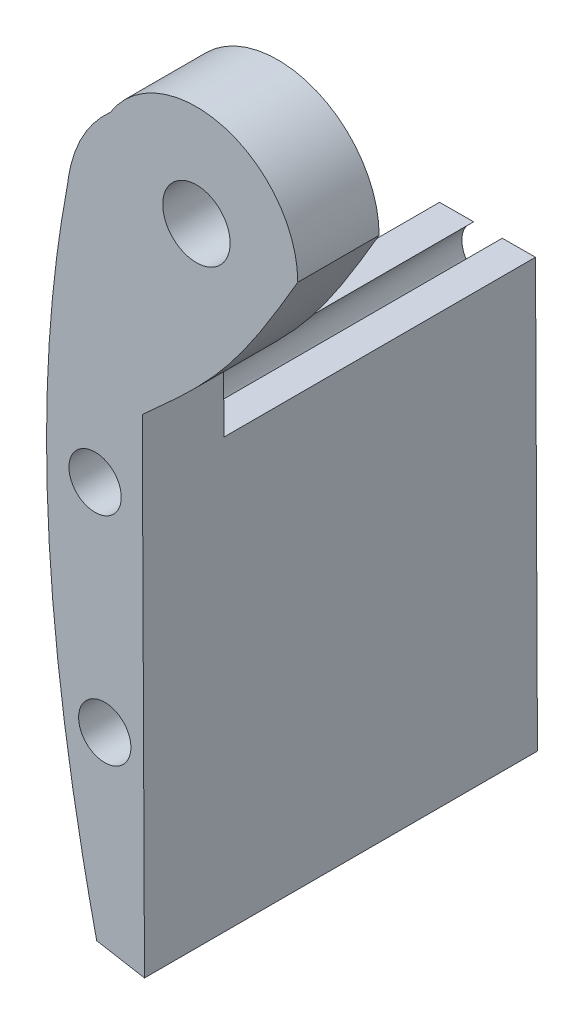
SolidWorks part; units mm, degrees
ref_plane "Front Plane" through (0, 0, 0) normal (0, 0, 1) x (1, 0, 0)
ref_plane "Top Plane" through (0, 0, 0) normal (0, 1, 0) x (1, 0, 0)
ref_plane "Right Plane" through (0, 0, 0) normal (1, 0, 0) x (0, 0, -1)
sketch "Sketch1" plane through (0, 0, 0) normal (0, 0, 1) x (1, 0, 0)
  line L49 (-14.1534, -69.7169) -> (-10.0398, -70.4384)
  line L50 (-10.0398, -70.4384) -> (-10.2316, -28.5481)
  arc A48 (3.1505, -12) -> (-12.9862, -7.4065) centre (-5.5716, -12) ccw
  circle A49 centre (-5.5716, -12) radius 2.9
  spline S2 degree 3 poles (-18.4013, -30.5146) (-18.849, -43.6728) (-17.0302, -56.9394) (-14.1534, -69.7169) knots 0.288119 0.288119 0.288119 0.288119 1 1 1 1
  spline S3 degree 3 poles (-16.6639, -14.6308) (-17.6677, -19.8813) (-18.2201, -25.189) (-18.4013, -30.5146) knots 0 0 0 0 0.288119 0.288119 0.288119 0.288119
  spline S4 degree 2 poles (-16.6639, -14.6308) (-16.1578, -10.2368) (-12.9862, -7.4065) knots 0 0 0 1 1 1
  spline S5 degree 3 poles (3.1505, -12) (1.1214, -15.4485) (-2.5224, -21.6413) (-7.8644, -26.4273) (-10.2316, -28.5481) knots 0 0 0 0 0.556866 1 1 1 1
  dimension "D1" = 5.8
extrude "Boss-Extrude1" add sketch "Sketch1" against normal blind 7
sketch "Sketch2" plane through (0, 0, -7) normal (0, 0, -1) x (-1, 0, 0)
  line L2 (10.0398, -70.4384) -> (14.1534, -69.7169)
  line L3 (10.2079, -33.7171) -> (10.0398, -70.4384)
  line L4 (10.0398, -70.4384) -> (14.1534, -69.7169)
  line L5 (10.2079, -33.7171) -> (10.0398, -70.4384)
  line L14 (13.0668, -33.7302) -> (10.2079, -33.7171)
  line L15 (13.0668, -33.7302) -> (10.2079, -33.7171)
  line L16 (18.4664, -33.7549) -> (15.5326, -33.7414)
  line L17 (18.4664, -33.7549) -> (15.5326, -33.7414)
  arc A2 (13.0668, -33.7302) -> (15.5326, -33.7414) centre (14.2911, -35.6179) ccw
  arc A3 (13.0668, -33.7302) -> (15.5326, -33.7414) centre (14.2911, -35.6179) ccw
  spline S1 degree 3 poles (1784.7335, 855.5068) (-2007.9635, -1350.9437) (2080.795, 905.4818) (-1947.5867, -284.5265) knots -8.573419 -8.573419 -8.573419 -8.573419 8.267818 8.267818 8.267818 8.267818 only from (14.1534, -69.7169) to (18.4664, -33.7549)
  spline S2 degree 3 poles (14.1534, -69.7169) (16.7942, -57.9876) (18.5434, -45.8463) (18.4664, -33.7549) knots 0.34652 0.34652 0.34652 0.34652 1 1 1 1
  dimension "D1" = 0
extrude "Boss-Extrude2" add sketch "Sketch2" along normal blind 26.8124
sketch "Sketch3" plane through (0, 0, 0) normal (0, 0, 1) x (1, 0, 0)
  circle A0 centre (-14.2911, -35.6179) radius 2.25
  circle A1 centre (-13.4597, -53.8503) radius 2.25
  dimension "D1" = 4.5
  dimension "D2" = 4.5
extrude "Cut-Extrude1" cut sketch "Sketch3" against normal through all
